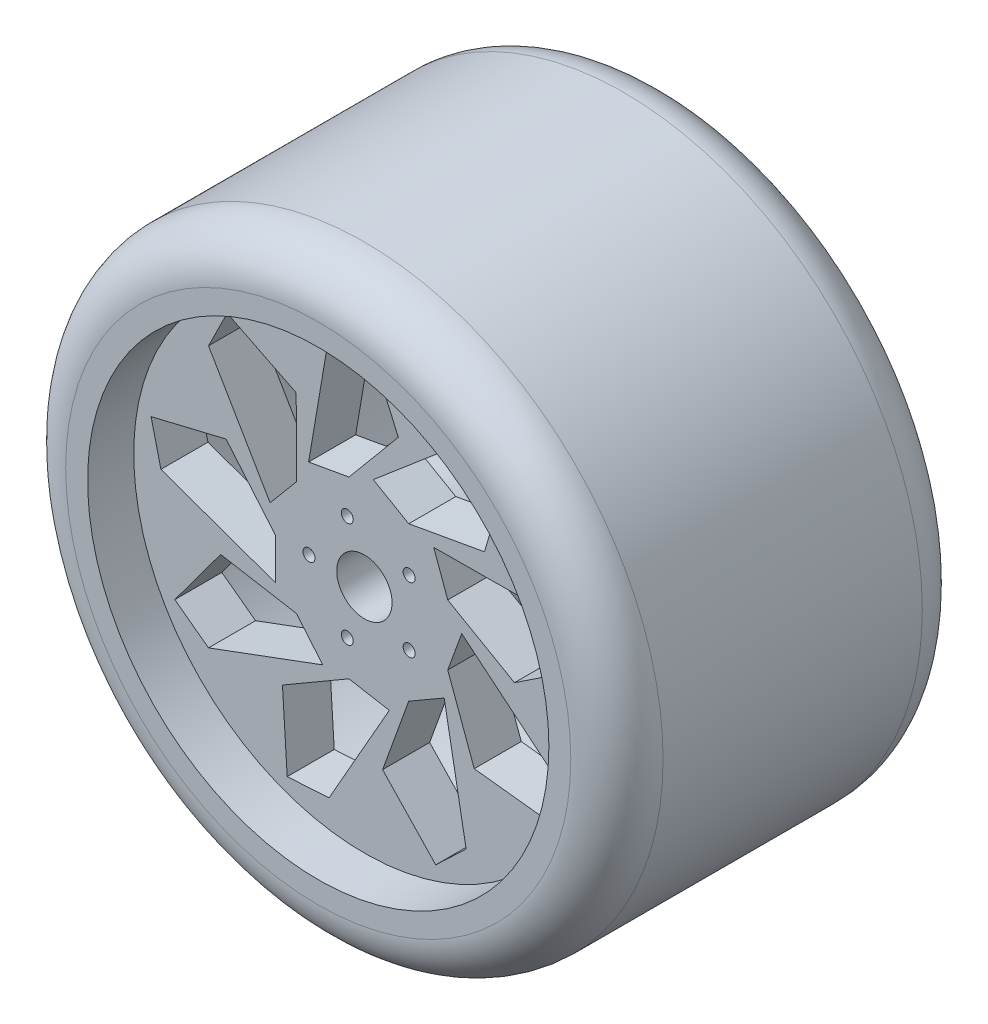
SolidWorks part; units mm, degrees
ref_plane "Płaszczyzna przednia" through (0, 0, 0) normal (0, 0, 1) x (1, 0, 0)
ref_plane "Płaszczyzna górna" through (0, 0, 0) normal (0, 1, 0) x (1, 0, 0)
ref_plane "Płaszczyzna prawa" through (0, 0, 0) normal (1, 0, 0) x (0, 0, -1)
sketch "Szkic1" plane through (0, 0, 0) normal (0, 0, 1) x (1, 0, 0)
  circle A0 centre (0, 0) radius 323.75
  dimension "D1" = 647.5
extrude "Dodanie-wyciągnięcie1" add sketch "Szkic1" along normal blind 381
fillet "Zaokrąglenie1" radius 50 2 edges at (323.75, 0, 0) (323.75, 0, 381)
sketch "Szkic2" plane through (0, 0, 381) normal (0, 0, 1) x (1, 0, 0)
  circle A0 centre (-60, 0) radius 6.5
  circle A1 centre (-18.541, 57.0634) radius 6.5
  circle A2 centre (48.541, 35.2671) radius 6.5
  circle A3 centre (48.541, -35.2671) radius 6.5
  circle A4 centre (-18.541, -57.0634) radius 6.5
  circle A5 centre (0, 0) radius 30
  point P14 (0, 0)
  dimension "D2" = 13
  dimension "D4" = 60
  dimension "D1" = 60
  dimension "D3" = 5
  dimension "D5" = 60
extrude "Wytnij-wyciągnięcie1" cut sketch "Szkic2" against normal through all
sketch "Szkic3" plane through (0, 0, 381) normal (0, 0, 1) x (1, 0, 0)
  circle A0 centre (0, 0) radius 250
  dimension "D1" = 500
extrude "Wytnij-wyciągnięcie2" cut sketch "Szkic3" against normal blind 50
sketch "Szkic4" plane through (0, 0, 0) normal (0, 0, -1) x (-1, 0, 0)
  circle A0 centre (0, 0) radius 250
  dimension "D1" = 500
extrude "Wytnij-wyciągnięcie3" cut sketch "Szkic4" against normal blind 200
sketch "Szkic5" plane through (0, 0, 331) normal (0, 0, 1) x (1, 0, 0)
  line L0 (-96.1558, 0) -> (-149.9257, 63.746)
  line L1 (-149.9257, 63.746) -> (-231.1914, 44.1934)
  line L2 (-231.1914, 44.1934) -> (-220.5585, 0)
  line L3 (-220.5585, 0) -> (-96.1558, -44.4046)
  line L4 (-96.1558, -44.4046) -> (-96.1558, 0)
  line L5 (-102.2024, 27.7918) -> (-73.6596, 61.8078)
  line L6 (-73.6596, 61.8078) -> (-73.8746, 145.2027)
  line L7 (-73.8746, 145.2027) -> (-148.696, 182.4611)
  line L8 (-148.696, 182.4611) -> (-168.9576, 141.7722)
  line L9 (-168.9576, 141.7722) -> (-102.2024, 27.7918)
  line L10 (-60.4273, 86.9842) -> (-16.6973, 94.695)
  line L11 (-16.6973, 94.695) -> (36.7433, 158.7173)
  line L12 (36.7433, 158.7173) -> (3.376, 235.3532)
  line L13 (3.376, 235.3532) -> (-38.2996, 217.2077)
  line L14 (-38.2996, 217.2077) -> (-60.4273, 86.9842)
  line L15 (9.6224, 105.4757) -> (48.0779, 83.2734)
  line L16 (48.0779, 83.2734) -> (130.1685, 97.9664)
  line L17 (130.1685, 97.9664) -> (153.8683, 178.121)
  line L18 (153.8683, 178.121) -> (110.2792, 191.0092)
  line L19 (110.2792, 191.0092) -> (9.6224, 105.4757)
  line L20 (75.1696, 74.614) -> (90.3569, 32.8872)
  line L21 (90.3569, 32.8872) -> (162.6865, -8.6241)
  line L22 (162.6865, -8.6241) -> (232.3639, 37.5439)
  line L23 (232.3639, 37.5439) -> (207.2571, 75.4354)
  line L24 (207.2571, 75.4354) -> (75.1696, 74.614)
  line L25 (105.5442, 8.8395) -> (90.3569, -32.8872)
  line L26 (90.3569, -32.8872) -> (119.0816, -111.1793)
  line L27 (119.0816, -111.1793) -> (202.1339, -120.6003)
  line L28 (202.1339, -120.6003) -> (207.2571, -75.4354)
  line L29 (207.2571, -75.4354) -> (105.5442, 8.8395)
  line L30 (86.5335, -61.0711) -> (48.0779, -83.2734)
  line L31 (48.0779, -83.2734) -> (19.7571, -161.7125)
  line L32 (19.7571, -161.7125) -> (77.3231, -222.3144)
  line L33 (77.3231, -222.3144) -> (110.2792, -191.0092)
  line L34 (110.2792, -191.0092) -> (86.5335, -61.0711)
  line L35 (27.0328, -102.4058) -> (-16.6973, -94.695)
  line L36 (-16.6973, -94.695) -> (-88.8119, -136.5786)
  line L37 (-88.8119, -136.5786) -> (-83.668, -220.005)
  line L38 (-83.668, -220.005) -> (-38.2996, -217.2077)
  line L39 (-38.2996, -217.2077) -> (27.0328, -102.4058)
  line L40 (-45.1169, -95.8237) -> (-73.6596, -61.8078)
  line L41 (-73.6596, -61.8078) -> (-155.8249, -47.5381)
  line L42 (-155.8249, -47.5381) -> (-205.5099, -114.7529)
  line L43 (-205.5099, -114.7529) -> (-168.9576, -141.7722)
  line L44 (-168.9576, -141.7722) -> (-45.1169, -95.8237)
  point P48 (0, 0)
  dimension "D1" = 9
extrude "Wytnij-wyciągnięcie4" cut sketch "Szkic5" against normal blind 200
sketch "Szkic6" plane through (0, 0, 200) normal (0, 0, -1) x (-1, 0, 0)
  circle A0 centre (0, 0) radius 250
  circle A1 centre (0, 0) radius 85
  dimension "D1" = 170
extrude "Wytnij-wyciągnięcie5" cut sketch "Szkic6" against normal blind 80
